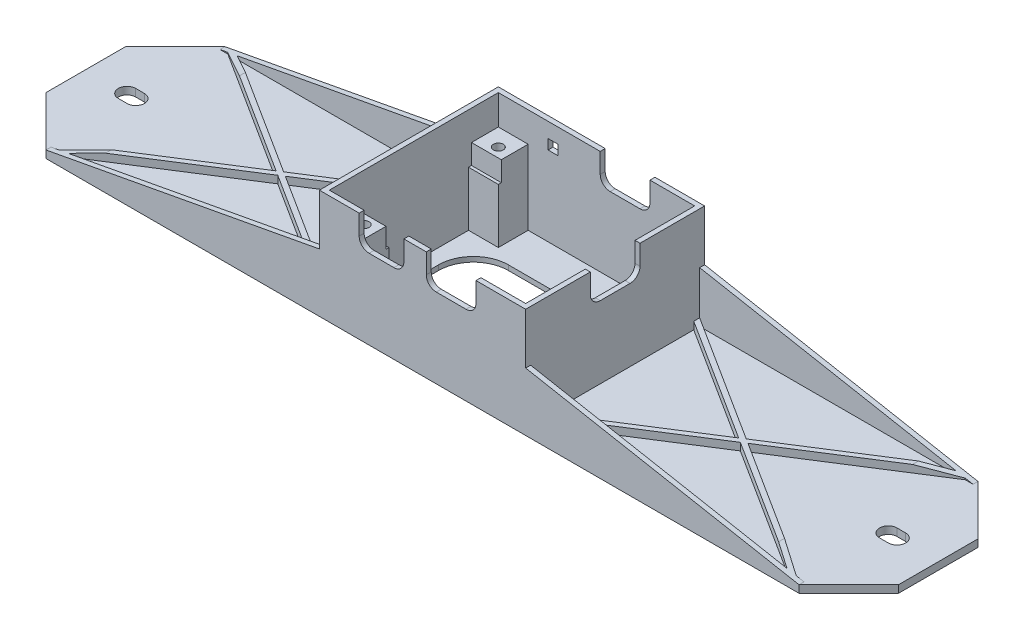
SolidWorks part; units mm, degrees
ref_plane "Front Plane" through (0, 0, 0) normal (0, 0, 1) x (1, 0, 0)
ref_plane "Top Plane" through (0, 0, 0) normal (0, 1, 0) x (1, 0, 0)
ref_plane "Right Plane" through (0, 0, 0) normal (1, 0, 0) x (0, 0, -1)
sketch "Sketch1" plane through (0, 0, 0) normal (0, 1, 0) x (1, 0, 0)
  line L1 (-10.8398, 23.3657) -> (-4.8398, 23.3657)
  line L2 (-10.8398, 23.3657) -> (-10.8398, 17.3657)
  line L5 (-10.8398, 23.3657) -> (-4.8398, 17.3657) construction
  line L6 (-9.8398, 17.3657) -> (-4.8398, 22.3657) construction
  line L7 (22.6602, 23.3657) -> (28.6602, 23.3657)
  line L10 (28.6602, 23.3657) -> (28.6602, 17.3657)
  line L11 (22.6602, 22.3657) -> (27.6602, 17.3657) construction
  line L12 (22.6602, 17.3657) -> (28.6602, 23.3657) construction
  line L14 (-10.8398, -4.6343) -> (-10.8398, -10.6343)
  line L15 (-10.8398, -10.6343) -> (-4.8398, -10.6343)
  line L17 (-9.8398, -4.6343) -> (-4.8398, -9.6343) construction
  line L18 (-10.8398, -10.6343) -> (-4.8398, -4.6343) construction
  line L21 (22.6604, -10.6343) -> (28.6604, -10.6343)
  line L22 (28.6604, -4.6343) -> (28.6604, -10.6343)
  line L23 (22.6604, -4.6343) -> (28.6604, -10.6343) construction
  line L24 (22.6604, -9.6343) -> (27.6604, -4.6343) construction
  line L28 (-4.8398, 23.3657) -> (-4.8398, 17.3657)
  line L31 (-10.8398, 17.3657) -> (-4.8398, 17.3657)
  line L36 (22.6602, 23.3657) -> (22.6602, 17.3657)
  line L39 (22.6602, 17.3657) -> (28.6602, 17.3657)
  line L43 (-10.8398, -4.6343) -> (-4.8398, -4.6343)
  line L48 (-4.8398, -4.6343) -> (-4.8398, -10.6343)
  line L51 (22.6604, -4.6343) -> (28.6604, -4.6343)
  line L56 (22.6604, -4.6343) -> (22.6604, -10.6343)
  circle A0 centre (-7.3398, 19.8657) radius 1
  circle A1 centre (25.1602, 19.8657) radius 1
  circle A2 centre (25.1604, -7.1343) radius 1
  circle A3 centre (-7.3398, -7.1343) radius 1
  dimension "D1" = 2
  dimension "D2" = 2
  dimension "D3" = 2
  dimension "D4" = 2
  dimension "D5" = 27
  dimension "D6" = 27
  dimension "D7" = 32.5
  dimension "D8" = 3.5
  dimension "D9" = 3.5
  dimension "D10" = 2.5
  dimension "D11" = 3.5
  dimension "D12" = 3.5
  dimension "D13" = 2.5
  dimension "D14" = 3.5
  dimension "D15" = 3.5
  dimension "D16" = 2.5
  dimension "D17" = 3.5
  dimension "D18" = 3.5
  dimension "D19" = 2.5
  dimension "D20" = 0
extrude "Boss-Extrude1" add sketch "Sketch1" along normal blind 15
sketch "Sketch2" plane through (0, 0, 0) normal (0, -1, 0) x (1, 0, 0)
  line L1 (-10.8398, 10.6343) -> (28.6602, 10.6343)
  line L2 (-10.8398, 10.6343) -> (-10.8398, -23.3657)
  line L3 (-10.8398, -23.3657) -> (28.6602, -23.3657)
  line L4 (28.6602, 10.6343) -> (28.6602, -23.3657)
extrude "Boss-Extrude2" add sketch "Sketch2" along normal blind 1
sketch "Sketch3" plane through (0, -1, 0) normal (0, -1, 0) x (1, 0, 0)
  line L1 (-10.8398, 10.6343) -> (28.6602, 10.6343)
  line L2 (-11.8398, 9.7302) -> (-11.8398, 11.6343)
  line L3 (-11.8398, 11.6343) -> (29.6602, 11.6343)
  line L4 (29.6602, 9.7302) -> (29.6602, 11.6343)
  line L6 (29.6602, 9.7302) -> (29.6602, -24.3657)
  line L7 (29.6602, -24.3657) -> (28.8037, -24.3657)
  line L8 (28.6602, 10.6343) -> (28.6602, -23.3657)
  line L9 (28.8037, -24.3657) -> (-10.6963, -24.3657)
  line L11 (28.6602, -23.3657) -> (-10.8398, -23.3657)
  line L14 (-11.8398, 9.7302) -> (-11.8398, -24.3657)
  line L15 (-11.8398, -24.3657) -> (-10.6963, -24.3657)
  line L16 (-10.8398, 10.6343) -> (-10.8398, -23.3657)
  dimension "D1" = 1
  dimension "D2" = 1
  dimension "D3" = 1
  dimension "D4" = 1
extrude "Boss-Extrude3" add sketch "Sketch3" against normal blind 22
sketch "Sketch4" plane through (0, 0, 0) normal (0, 1, 0) x (1, 0, 0)
  line L0 (-10.8398, 23.3657) -> (28.6602, 23.3657) construction
  line L1 (-7.8398, 15.3657) -> (28.6602, 15.3657)
  line L2 (-7.8398, 15.3657) -> (-7.8398, -2.6343)
  line L3 (-7.8398, -2.6343) -> (28.6602, -2.6343)
  line L4 (28.6602, 15.3657) -> (28.6602, -2.6343)
  line L5 (22.6604, -10.6343) -> (-4.8398, -10.6343) construction
  line L6 (28.6602, 17.3657) -> (28.6602, -4.6343) construction
  line L7 (-10.8398, -4.6343) -> (-10.8398, 17.3657) construction
  dimension "D1" = 8
  dimension "D2" = 8
  dimension "D3" = 0
  dimension "D4" = 3
extrude "Cut-Extrude1" cut sketch "Sketch4" against normal blind 22
fillet "Fillet1" radius 7 4 edges at (-7.8398, -0.5, -15.3657) (-7.8398, -0.5, 2.6343) (28.6602, -0.5, -15.3657) (28.6602, -0.5, 2.6343)
sketch "Sketch7" plane through (0, 15, 0) normal (0, 1, 0) x (1, 0, 0)
  line L0 (-10.8398, -10.6343) -> (-10.8398, 23.3657) construction
  line L1 (-4.8398, 17.3657) -> (-10.8398, 17.3657)
  line L2 (-4.8398, 17.3657) -> (-4.8398, 17.9657)
  line L3 (-4.8398, 17.9657) -> (-10.8398, 17.9657)
  line L4 (-10.8398, 17.3657) -> (-10.8398, 17.9657)
  line L5 (-10.8398, -4.6343) -> (-10.8398, -10.6343) construction
  line L6 (-4.8398, -4.6343) -> (-10.8398, -4.6343)
  line L7 (-4.8398, -4.6343) -> (-4.8398, -5.2343)
  line L8 (-4.8398, -5.2343) -> (-10.8398, -5.2343)
  line L9 (-10.8398, -4.6343) -> (-10.8398, -5.2343)
  dimension "D1" = 0.6
  dimension "D2" = 0.6
extrude "Cut-Extrude2" cut sketch "Sketch7" against normal blind 4
sketch "Sketch8" plane through (28.6602, 0, 0) normal (-1, 0, 0) x (0, 0, 1)
  line L0 (-23.3657, 21) -> (10.6343, 21) construction
  line L1 (-11.3657, 15) -> (-1.3657, 15)
  line L2 (-11.3657, 15) -> (-11.3657, 21)
  line L3 (-11.3657, 21) -> (-1.3657, 21)
  line L4 (-1.3657, 15) -> (-1.3657, 21)
  line L6 (-17.3657, 15) -> (-17.3657, 0) construction
  line L7 (4.6343, 0) -> (4.6343, 15) construction
  dimension "D1" = 6
  dimension "D2" = 6
extrude "Cut-Extrude3" cut sketch "Sketch8" against normal blind 4
fillet "Fillet2" radius 2 2 edges at (29.1602, 15, -1.3657) (29.1602, 15, -11.3657)
sketch "Sketch9" plane through (0, 0, 10.6343) normal (0, 0, -1) x (-1, 0, 0)
  line L0 (-28.6602, 21) -> (10.8398, 21) construction
  line L1 (-19.6604, 15) -> (-9.6604, 15)
  line L2 (-19.6604, 15) -> (-19.6604, 21)
  line L3 (-19.6604, 21) -> (-9.6604, 21)
  line L4 (-9.6604, 15) -> (-9.6604, 21)
  line L5 (-22.6604, 15) -> (-22.6604, 0) construction
  line L6 (-5.1602, 15) -> (3.8398, 15)
  line L7 (-5.1602, 15) -> (-5.1602, 21)
  line L8 (-5.1602, 21) -> (3.8398, 21)
  line L9 (3.8398, 15) -> (3.8398, 21)
  line L10 (4.8398, 15) -> (4.8398, 0) construction
  dimension "D1" = 3
  dimension "D2" = 10
  dimension "D3" = 1
  dimension "D4" = 9
extrude "Cut-Extrude4" cut sketch "Sketch9" against normal blind 4
fillet "Fillet3" radius 2 4 edges at (5.1602, 15, 11.1343) (-3.8398, 15, 11.1343) (9.6604, 15, 11.1343) (19.6604, 15, 11.1343)
sketch "Sketch10" plane through (0, 0, -23.3657) normal (0, 0, 1) x (1, 0, 0)
  line L0 (-10.8398, 21) -> (28.6602, 21) construction
  line L1 (19.6602, 15) -> (9.6602, 15)
  line L2 (19.6602, 15) -> (19.6602, 21)
  line L3 (19.6602, 21) -> (9.6602, 21)
  line L4 (9.6602, 15) -> (9.6602, 21)
  line L5 (22.6602, 15) -> (22.6602, 0) construction
  dimension "D1" = 3
  dimension "D2" = 10
extrude "Cut-Extrude5" cut sketch "Sketch10" against normal blind 4
fillet "Fillet4" radius 2 2 edges at (19.6602, 15, -23.8657) (9.6602, 15, -23.8657)
sketch "Sketch11" plane through (0, 0, -23.3657) normal (0, 0, 1) x (1, 0, 0)
  line L0 (-4.8398, 15) -> (-10.8398, 15) construction
  line L1 (-0.8398, 18) -> (1.1602, 18)
  line L2 (-0.8398, 18) -> (-0.8398, 16)
  line L3 (-0.8398, 16) -> (1.1602, 16)
  line L4 (1.1602, 18) -> (1.1602, 16)
  line L5 (-4.8398, 15) -> (-4.8398, 0) construction
  dimension "D1" = 1
  dimension "D2" = 2
  dimension "D3" = 2
  dimension "D4" = 4
extrude "Cut-Extrude6" cut sketch "Sketch11" against normal blind 4
sketch "Sketch12" plane through (-11.8398, 0, 0) normal (-1, 0, 0) x (0, 0, 1)
  line L0 (11.6343, 21) -> (11.6343, -1) construction
  line L1 (-24.3657, -1) -> (11.6343, -1)
  line L2 (-24.3657, -1) -> (-24.3657, 0.5)
  line L3 (-24.3657, 0.5) -> (11.6343, 0.5)
  line L4 (11.6343, -1) -> (11.6343, 0.5)
  dimension "D1" = 1.5
extrude "Boss-Extrude4" add sketch "Sketch12" along normal blind 65
sketch "Sketch13" plane through (29.6602, 0, 0) normal (1, 0, 0) x (0, 0, -1)
  line L0 (24.3657, 21) -> (24.3657, -1) construction
  line L1 (-11.6343, -1) -> (24.3657, -1)
  line L2 (-11.6343, -1) -> (-11.6343, 0.5)
  line L3 (-11.6343, 0.5) -> (24.3657, 0.5)
  line L4 (24.3657, -1) -> (24.3657, 0.5)
  dimension "D1" = 1.5
extrude "Boss-Extrude5" add sketch "Sketch13" along normal blind 65
sketch "Sketch14" plane through (0, 0.5, 0) normal (0, 1, 0) x (1, 0, 0)
  line L1 (-76.8398, -11.6343) -> (-76.8398, 24.3657) construction
  line L2 (-68.5398, 8.1157) -> (-66.7898, 8.1157)
  line L3 (-68.5398, 4.6157) -> (-66.7898, 4.6157)
  line L4 (84.6102, 8.1157) -> (86.3602, 8.1157)
  line L5 (84.6102, 4.6157) -> (86.3602, 4.6157)
  arc A0 (-68.5398, 8.1157) -> (-68.5398, 4.6157) centre (-68.5398, 6.3657) ccw
  arc A1 (86.3602, 4.6157) -> (86.3602, 8.1157) centre (86.3602, 6.3657) ccw
  arc A2 (-66.7898, 4.6157) -> (-66.7898, 8.1157) centre (-66.7898, 6.3657) ccw
  arc A3 (84.6102, 8.1157) -> (84.6102, 4.6157) centre (84.6102, 6.3657) ccw
  dimension "D1" = 3.5
  dimension "D2" = 151.4
  dimension "D3" = 3.5
  dimension "D4" = 8.3
extrude "Cut-Extrude7" cut sketch "Sketch14" against normal blind 65
chamfer "Chamfer1" distance 10 angle 45 4 edges at (-76.8398, -0.25, -24.3657) (-76.8398, -0.25, 11.6343) (94.6602, -0.25, -24.3657) (94.6602, -0.25, 11.6343)
sketch "Sketch15" plane through (0, 0, 11.6343) normal (0, 0, 1) x (1, 0, 0)
  line L0 (-66.8398, 0.5) -> (-11.8398, 10.75)
  line L1 (-11.8398, 21) -> (-11.8398, 0.5) construction
  line L2 (-11.8398, 10.75) -> (-11.8398, 0.5)
  line L3 (-11.8398, 0.5) -> (-66.8398, 0.5)
  line L4 (29.6602, 10.75) -> (84.6602, 0.5)
  line L5 (29.6602, 21) -> (29.6602, 0.5) construction
  line L6 (84.6602, 0.5) -> (29.6602, 0.5)
  line L7 (29.6602, 0.5) -> (29.6602, 10.75)
extrude "Boss-Extrude6" add sketch "Sketch15" against normal blind 1
sketch "Sketch16" plane through (0, 0, -24.3657) normal (0, 0, -1) x (-1, 0, 0)
  line L0 (-29.6602, 10.75) -> (-84.6602, 0.5)
  line L1 (-84.6602, 0.5) -> (-29.6602, 0.5)
  line L2 (-29.6602, 0.5) -> (-29.6602, 10.75)
  line L3 (11.8398, 10.75) -> (66.8398, 0.5)
  line L4 (66.8398, 0.5) -> (11.8398, 0.5)
  line L5 (11.8398, 0.5) -> (11.8398, 10.75)
extrude "Boss-Extrude7" add sketch "Sketch16" against normal blind 1
sketch "Sketch17" plane through (0, 0.5, 0) normal (0, 1, 0) x (1, 0, 0)
  line L0 (-11.8398, 23.3657) -> (-37.6227, 6.9583)
  line L1 (-66.8398, -11.6343) -> (-64.9771, -11.6343)
  line L2 (-11.8398, -11.6343) -> (-66.8398, -11.6343) construction
  line L3 (-64.9771, -11.6343) -> (-37.6227, 5.773)
  line L4 (-11.8398, -10.6343) -> (-11.8398, 23.3657) construction
  line L5 (-11.8398, 22.1804) -> (-11.8398, 23.3657)
  line L6 (-11.8398, -10.6343) -> (-37.6227, 5.773)
  line L7 (-66.8398, 24.3657) -> (-64.9771, 24.3657)
  line L8 (-66.8398, 24.3657) -> (-11.8398, 24.3657) construction
  line L9 (-64.9771, 24.3657) -> (-37.6227, 6.9583)
  line L10 (-11.8398, -11.6343) -> (-11.8398, 24.3657) construction
  line L11 (-11.8398, -9.449) -> (-11.8398, -10.6343)
  line L12 (29.6602, 23.3657) -> (55.4432, 6.9583)
  line L13 (84.6602, -11.6343) -> (82.7976, -11.6343)
  line L14 (84.6602, -11.6343) -> (29.6602, -11.6343) construction
  line L15 (82.7976, -11.6343) -> (55.4432, 5.773)
  line L16 (29.6602, 24.3657) -> (29.6602, 11.3657) construction
  line L17 (29.6602, 22.1804) -> (29.6602, 23.3657)
  line L18 (29.6602, -10.6343) -> (55.4432, 5.773)
  line L19 (84.6602, 24.3657) -> (82.7976, 24.3657)
  line L20 (29.6602, 24.3657) -> (84.6602, 24.3657) construction
  line L21 (82.7976, 24.3657) -> (55.4432, 6.9583)
  line L22 (29.6602, 23.3657) -> (29.6602, -10.6343) construction
  line L23 (29.6602, -9.449) -> (29.6602, -10.6343)
  line L24 (-36.6914, 6.3657) -> (-11.8398, -9.449)
  line L25 (-38.5541, 6.3657) -> (-66.8398, -11.6343)
  line L26 (-38.5541, 6.3657) -> (-66.8398, 24.3657)
  line L27 (-36.6914, 6.3657) -> (-11.8398, 22.1804)
  line L28 (56.3745, 6.3657) -> (84.6602, -11.6343)
  line L29 (54.5119, 6.3657) -> (29.6602, 22.1804)
  line L30 (54.5119, 6.3657) -> (29.6602, -9.449)
  line L31 (56.3745, 6.3657) -> (84.6602, 24.3657)
  dimension "D1" = 1
  dimension "D2" = 1
  dimension "D3" = 1
  dimension "D4" = 1
extrude "Boss-Extrude8" add sketch "Sketch17" along normal blind 1.5
sketch "Sketch18" plane through (0, 0, 11.6343) normal (0, 0, 1) x (1, 0, 0)
  line L0 (-57.5764, 2.2264) -> (-66.8398, 0.5)
  line L1 (-11.8398, 10.75) -> (-64.9771, 0.8471) construction
  line L2 (-66.8398, 0.5) -> (-66.8398, 4.2878)
  line L3 (-66.8398, 4.2878) -> (-57.5764, 2.2264)
  line L4 (75.7922, 2.1527) -> (84.6602, 0.5)
  line L5 (82.7976, 0.8471) -> (29.6602, 10.75) construction
  line L6 (84.6602, 0.5) -> (84.6602, 4.2878)
  line L7 (84.6602, 4.2878) -> (75.7922, 2.1527)
extrude "Cut-Extrude8" cut sketch "Sketch18" against normal blind 51.5
